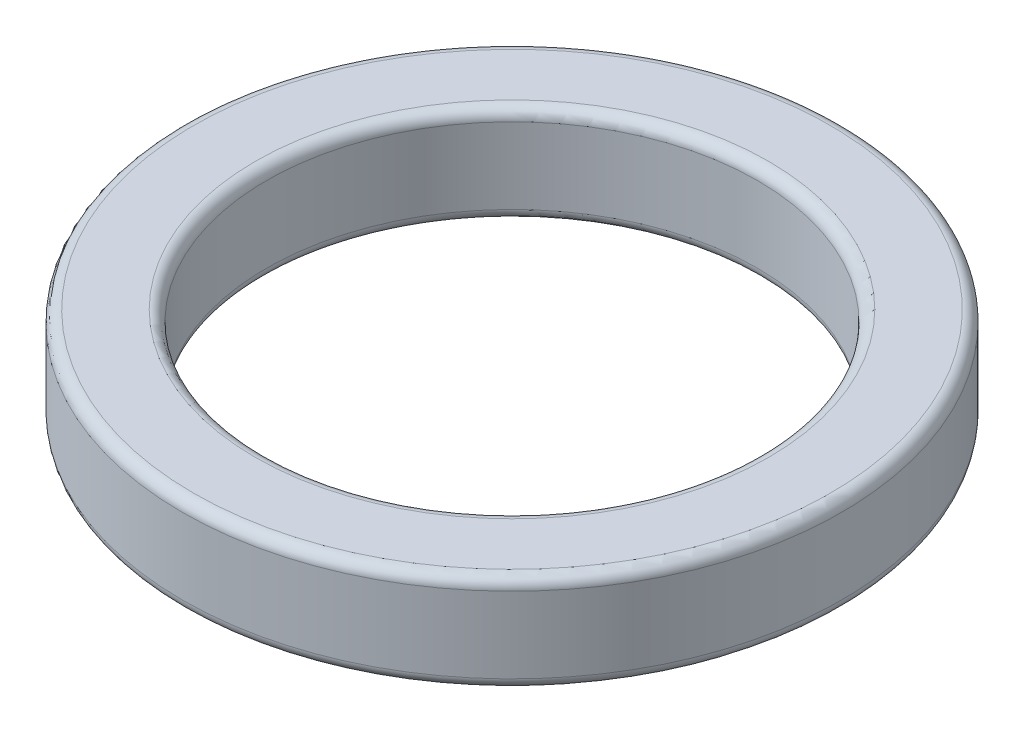
SolidWorks part; units mm, degrees
material "6061-T6 (SS)"
ref_plane "Front Plane" through (0, 0, 0) normal (0, 0, 1) x (1, 0, 0)
ref_plane "Top Plane" through (0, 0, 0) normal (0, 1, 0) x (1, 0, 0)
ref_plane "Right Plane" through (0, 0, 0) normal (1, 0, 0) x (0, 0, -1)
sketch "Sketch1" plane through (0, 0, 0) normal (0, 1, 0) x (1, 0, 0)
  circle A0 centre (0, 0) radius 17.5
  circle A1 centre (0, 0) radius 23.5
  dimension "D1" = 47
  dimension "D2" = 35
extrude "Boss-Extrude1" add sketch "Sketch1" along normal mid plane 7
fillet "Fillet1" radius 0.7937 4 edges at (0, -3.5, 17.5) (0, -3.5, 23.5) (0, 3.5, 17.5) (0, 3.5, 23.5)
